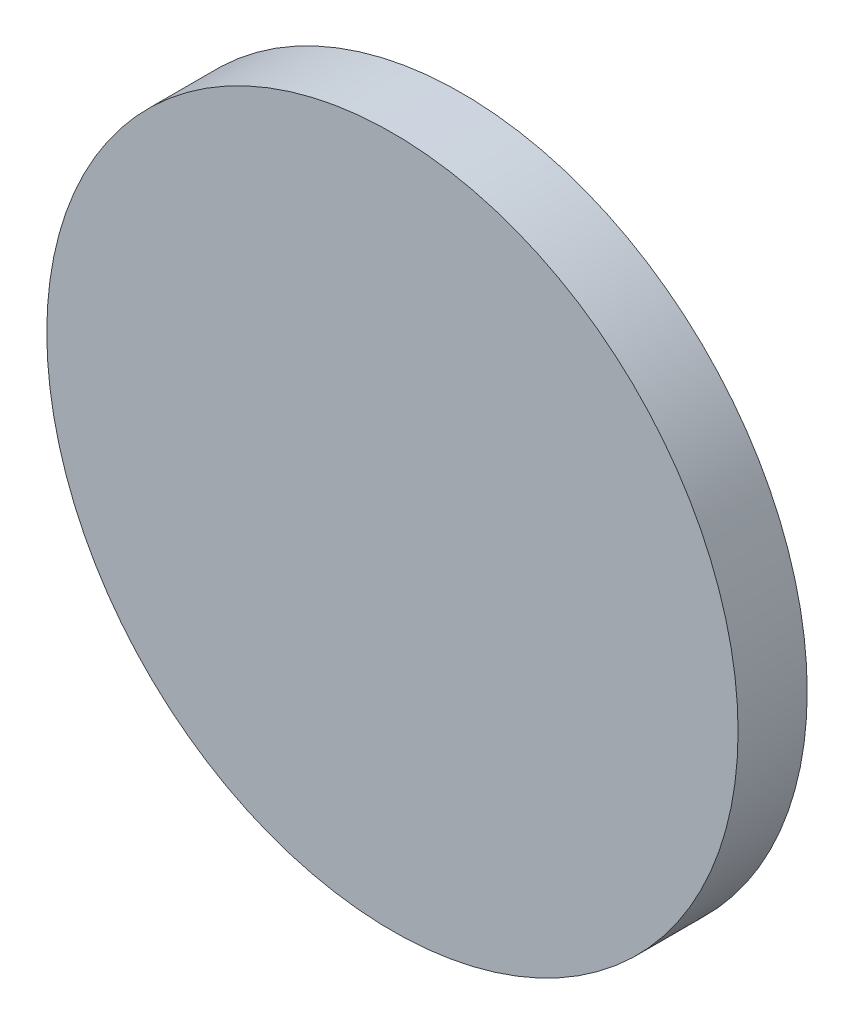
SolidWorks part; units mm, degrees
ref_plane "Plan de face" through (0, 0, 0) normal (0, 0, 1) x (1, 0, 0)
ref_plane "Plan de dessus" through (0, 0, 0) normal (0, 1, 0) x (1, 0, 0)
ref_plane "Plan de droite" through (0, 0, 0) normal (1, 0, 0) x (0, 0, -1)
sketch "Esquisse1" plane through (0, 0, 0) normal (0, 0, 1) x (1, 0, 0)
  circle A0 centre (0, 0) radius 30
  dimension "D1" = 60
extrude "Boss.-Extru.1" add sketch "Esquisse1" along normal blind 6
